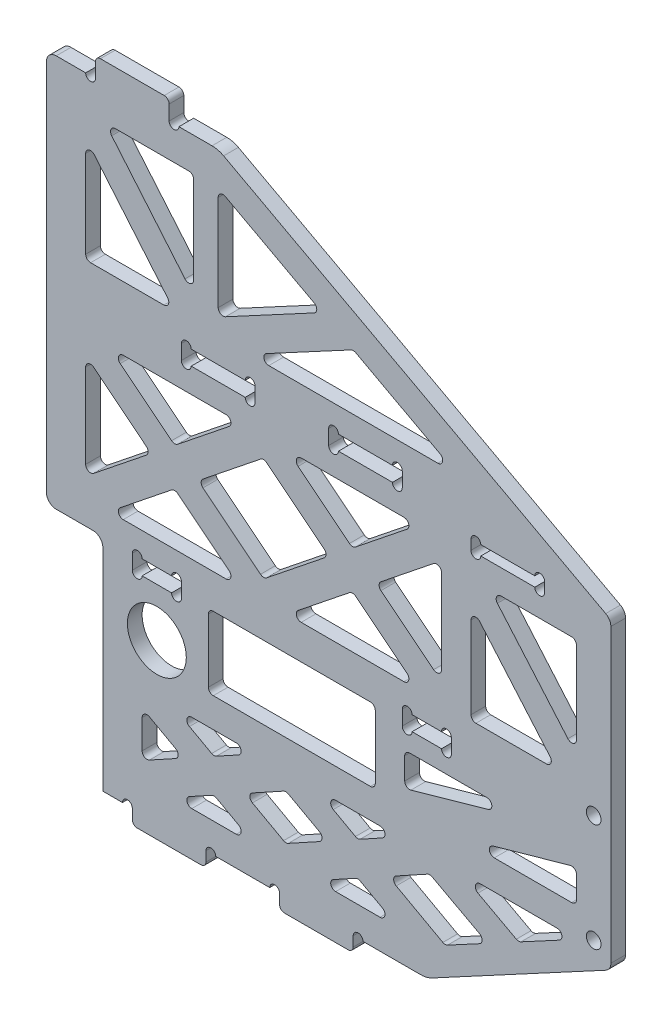
SolidWorks part; units mm, degrees
material "Thornel Mat VMA"
ref_plane "前视基准面" through (0, 0, 0) normal (0, 0, 1) x (1, 0, 0)
ref_plane "上视基准面" through (0, 0, 0) normal (0, 1, 0) x (1, 0, 0)
ref_plane "右视基准面" through (0, 0, 0) normal (1, 0, 0) x (0, 0, -1)
sketch "草图1" plane through (0, 0, 0) normal (0, 0, 1) x (1, 0, 0)
  line L0 (17.5, 83) -> (97.5, 40)
  line L1 (0, 0) -> (10, 0)
  line L2 (0, 0) -> (0, 3)
  line L3 (0, 3) -> (10, 3)
  line L4 (10, 0) -> (10, 3)
  line L5 (-17.5, 83) -> (-7.5, 83)
  line L11 (97.5, -21.8) -> (60, -42)
  line L12 (0, -42) -> (-6, -42)
  line L13 (0, -42) -> (0, 0) construction
  line L15 (97.5, -21.8) -> (97.5, 40)
  line L17 (97.5, 40) -> (84, 40) construction
  line L18 (-6, 3) -> (-6, -42)
  line L20 (55, 0) -> (65, 0)
  line L21 (65, 0) -> (65, 3)
  line L22 (65, 3) -> (55, 3)
  line L23 (55, 3) -> (55, 0)
  line L25 (94, -18.3) -> (94, 3.7) construction
  line L27 (7.5, 83) -> (7.5, 87)
  line L28 (40, 42) -> (55, 42)
  line L29 (55, 42) -> (55, 45)
  line L30 (55, 45) -> (40, 45)
  line L31 (40, 45) -> (40, 42)
  line L36 (45, -45) -> (45, -42)
  line L37 (45, -45) -> (30, -45)
  line L38 (60, -42) -> (45, -42)
  line L39 (30, -45) -> (30, -42)
  line L40 (30, -42) -> (15, -42)
  line L41 (15, -45) -> (15, -42)
  line L42 (15, -45) -> (0, -45)
  line L43 (0, -45) -> (0, -42)
  line L44 (10, 42) -> (25, 42)
  line L45 (25, 42) -> (25, 45)
  line L46 (25, 45) -> (10, 45)
  line L47 (10, 45) -> (10, 42)
  line L48 (-6, 3) -> (-17.5, 3)
  line L49 (-17.5, 3) -> (-17.5, 83)
  line L50 (7.5, 87) -> (-7.5, 87)
  line L51 (-7.5, 83) -> (-7.5, 87)
  line L52 (7.5, 83) -> (17.5, 83)
  line L60 (69, 38) -> (84, 38)
  line L61 (84, 38) -> (84, 40)
  line L62 (84, 40) -> (69, 40)
  line L63 (69, 40) -> (69, 38)
  circle A2 centre (94, -18.3) radius 1.5
  circle A3 centre (94, 3.7) radius 1.5
  dimension "D15" = 94
  dimension "D16" = 23.7
  dimension "D17" = 61.8
  dimension "D18" = 3.5
  dimension "D19" = 3
  dimension "D20" = 3.5
  dimension "D1" = 3
  dimension "D2" = 45
  dimension "D3" = 10
  dimension "D4" = 42
  dimension "D5" = 6
  dimension "D6" = 3
  dimension "D7" = 15
  dimension "D8" = 15
  dimension "D9" = 11.5
  dimension "D10" = 10
  dimension "D11" = 80
  dimension "D12" = 35
  dimension "D13" = 4
  dimension "D14" = 15
  dimension "D21" = 15
  dimension "D22" = 3
  dimension "D23" = 15
  dimension "D24" = 39
  dimension "D25" = 10
  dimension "D26" = 22
  dimension "D27" = 13.5
  dimension "D28" = 15
  dimension "D29" = 2
extrude "凸台-拉伸1" add sketch "草图1" along normal blind 3
sketch "草图3" plane through (0, 0, 3) normal (0, 0, 1) x (1, 0, 0)
  line L0 (17.5, 76.1882) -> (17.5, 50)
  line L1 (17.5, 50) -> (66.2222, 50)
  line L2 (66.2222, 50) -> (17.5, 76.1882)
  line L3 (97.5, 40) -> (17.5, 83) construction
  line L4 (55, 45) -> (40, 45) construction
  line L5 (90.5, -13.8914) -> (90.5, -4)
  line L6 (-9.5, 76.1882) -> (12.5, 76.1882)
  line L7 (-9.5, 76.1882) -> (-9.5, 50)
  line L8 (-9.5, 50) -> (12.5, 50)
  line L9 (12.5, 76.1882) -> (12.5, 50)
  line L10 (-9.5, 37) -> (63, 37)
  line L11 (-9.5, 37) -> (-9.5, 8)
  line L12 (-9.5, 8) -> (63, 8)
  line L13 (63, 37) -> (63, 8)
  line L14 (69, 33) -> (90.5, 33)
  line L15 (69, 33) -> (69, 8)
  line L16 (69, 8) -> (90.5, 8)
  line L17 (90.5, 33) -> (90.5, 8)
  line L18 (2, -19.8914) -> (90.5, -19.8914)
  line L19 (2, -19.8914) -> (2, -36)
  line L20 (2, -36) -> (60.5954, -36)
  line L21 (90.5, -19.8914) -> (60.5954, -36)
  line L22 (15, -42) -> (30, -42) construction
  line L23 (-6, 3) -> (-6, -42) construction
  line L25 (10, 3) -> (0, 3) construction
  line L26 (-17.5, 83) -> (-17.5, 3) construction
  line L27 (40, 42) -> (55, 42) construction
  line L28 (65, 3) -> (55, 3) construction
  line L29 (97.5, -21.8) -> (97.5, 40) construction
  line L30 (69, 38) -> (84, 38) construction
  line L32 (60, -42) -> (97.5, -21.8) construction
  line L33 (69, 40) -> (69, 38) construction
  line L34 (15.5, 1) -> (49.5, 1)
  line L35 (15.5, 1) -> (15.5, -13.8914)
  line L36 (15.5, -13.8914) -> (49.5, -13.8914)
  line L37 (49.5, 1) -> (49.5, -13.8914)
  line L38 (10, 0) -> (10, 3) construction
  line L39 (55, 3) -> (55, 0) construction
  line L40 (55.5, -13.8914) -> (90.5, -13.8914)
  line L41 (55.5, -13.8914) -> (55.5, -4)
  line L42 (55.5, -4) -> (90.5, -4)
  line L43 (55, 0) -> (65, 0) construction
  circle A0 centre (5, -9.8914) radius 6
  dimension "D20" = 12
  dimension "D21" = 10
  dimension "D22" = 11
  dimension "D1" = 5
  dimension "D2" = 6
  dimension "D3" = 6
  dimension "D4" = 8
  dimension "D5" = 6
  dimension "D6" = 5
  dimension "D7" = 8
  dimension "D8" = 5
  dimension "D9" = 5
  dimension "D10" = 7
  dimension "D11" = 6
  dimension "D12" = 5
  dimension "D13" = 5
  dimension "D14" = 5
  dimension "D15" = 7
  dimension "D16" = 6
  dimension "D17" = 5.5
  dimension "D18" = 5.5
  dimension "D19" = 4
extrude "切除-拉伸2" cut sketch "草图3" against normal through all
sketch "草图4" plane through (0, 0, 3) normal (0, 0, 1) x (1, 0, 0)
  line L0 (-9.5, 76.1882) -> (12.5, 50)
  line L1 (17.5, 50) -> (45.0294, 64.797)
  line L2 (66.2222, 50) -> (17.5, 76.1882) construction
  line L3 (-9.5, 37) -> (26.75, 8)
  line L4 (-9.5, 8) -> (63, 8) construction
  line L5 (63, 8) -> (26.75, 37)
  line L6 (63, 37) -> (-9.5, 37) construction
  line L7 (26.75, 37) -> (-9.5, 8)
  line L8 (26.75, 8) -> (63, 37)
  line L9 (90.5, 8) -> (69, 33)
  line L10 (2, -19.8914) -> (31.2977, -36)
  line L11 (2, -36) -> (60.5954, -36) construction
  line L12 (60.5954, -36) -> (31.2977, -19.8914)
  line L13 (90.5, -19.8914) -> (2, -19.8914) construction
  line L14 (60.5954, -36) -> (63.2243, -37.4454)
  line L15 (60.5954, -19.8914) -> (31.2977, -36)
  line L16 (31.2977, -19.8914) -> (2, -36)
  line L17 (60.5954, -19.8914) -> (75.5477, -27.9457)
  line L18 (60.5954, -36) -> (90.5, -19.8914) construction
  line L19 (75.5477, -27.9457) -> (78.1889, -29.3684)
  line L20 (55.5, -13.8914) -> (90.5, -4)
  point P10 (41.8611, 63.0941)
  dimension "D1" = 3
  dimension "D2" = 3
extrude "拉伸-薄壁1" add sketch "草图4" against normal up to surface (3 mm away) thin up to face at (38.7739, -27.9457, 0) thin type mid plane wall 6
sketch "草图2" plane through (0, 0, 3) normal (0, 0, 1) x (1, 0, 0)
  line L0 (-7.5, 83) -> (-17.5, 83) construction
  line L1 (17.5, 83) -> (7.5, 83) construction
  line L2 (25, 45) -> (10, 45) construction
  line L3 (10, 42) -> (25, 42) construction
  line L4 (55, 45) -> (40, 45) construction
  line L5 (40, 42) -> (55, 42) construction
  line L6 (84, 40) -> (69, 40) construction
  line L7 (69, 38) -> (84, 38) construction
  line L8 (10, 3) -> (0, 3) construction
  line L9 (0, 0) -> (10, 0) construction
  line L10 (65, 3) -> (55, 3) construction
  line L11 (55, 0) -> (65, 0) construction
  line L12 (-6, -42) -> (0, -42) construction
  line L13 (15, -42) -> (30, -42) construction
  line L14 (45, -42) -> (60, -42) construction
  line L15 (69, 38) -> (71, 38)
  line L16 (84, 40) -> (82, 40)
  line L17 (71, 40) -> (69, 40)
  line L18 (82, 38) -> (84, 38)
  circle A0 centre (-8.5, 83) radius 1
  circle A1 centre (8.5, 83) radius 1
  circle A2 centre (11, 45) radius 1
  circle A3 centre (24, 45) radius 1
  circle A4 centre (11, 42) radius 1
  circle A5 centre (24, 42) radius 1
  circle A6 centre (41, 45) radius 1
  circle A7 centre (41, 42) radius 1
  circle A8 centre (54, 45) radius 1
  circle A9 centre (54, 42) radius 1
  arc A10 (71, 40) -> (69, 40) centre (70, 40) ccw
  arc A11 (69, 38) -> (71, 38) centre (70, 38) ccw
  arc A12 (84, 40) -> (82, 40) centre (83, 40) ccw
  arc A13 (82, 38) -> (84, 38) centre (83, 38) ccw
  circle A14 centre (1, 3) radius 1
  circle A15 centre (1, 0) radius 1
  circle A16 centre (9, 3) radius 1
  circle A17 centre (9, 0) radius 1
  circle A18 centre (56, 3) radius 1
  circle A19 centre (56, 0) radius 1
  circle A20 centre (64, 3) radius 1
  circle A21 centre (64, 0) radius 1
  circle A22 centre (-1, -42) radius 1
  circle A23 centre (16, -42) radius 1
  circle A24 centre (29, -42) radius 1
  circle A25 centre (46, -42) radius 1
  dimension "D1" = 2
extrude "切除-拉伸1" cut sketch "草图2" against normal through all
fillet "圆角1" radius 1 82 edges at (30, -45, 1.5) (45, -45, 1.5) (15, -45, 1.5) (0, -45, 1.5) (7.5, 87, 1.5) (-7.5, 87, 1.5) (-5.5819, 76.1882, 1.5) (12.5, 76.1882, 1.5) (12.5, 54.664, 1.5) (-9.5, 50, 1.5) (-9.5, 71.5242, 1.5) (8.5819, 50, 1.5) (17.5, 53.4059, 1.5) (17.5, 76.1882, 1.5) (38.6928, 64.797, 1.5) (66.2222, 50, 1.5) (23.8366, 50, 1.5) (45.0294, 61.3911, 1.5) (26.75, 11.8419, 1.5) (13.4273, 22.5, 1.5) (26.75, 33.1581, 1.5) (40.0727, 22.5, 1.5) (31.5523, 8, 1.5) (44.875, 18.6581, 1.5) (58.1977, 8, 1.5) (-4.6977, 37, 1.5) (21.9477, 37, 1.5) (8.625, 18.6581, 1.5) (21.9477, 8, 1.5) (-4.6977, 8, 1.5) (49.6773, 22.5, 1.5) (63, 33.1581, 1.5) (63, 11.8419, 1.5) (-9.5, 33.1581, 1.5) (3.8227, 22.5, 1.5) (-9.5, 11.8419, 1.5) (58.1977, 37, 1.5) (44.875, 26.3419, 1.5) (31.5523, 37, 1.5) (86.5432, 8, 1.5) (69, 8, 1.5) (69, 28.3991, 1.5) (90.5, 33, 1.5) (90.5, 12.6009, 1.5) (72.9568, 33, 1.5) (31.2977, -23.315, 1.5) (39.7199, -27.9457, 1.5) (31.2977, -32.5764, 1.5) (22.8755, -27.9457, 1.5) (37.5244, -36, 1.5) (45.9466, -31.3693, 1.5) (52.1732, -27.9457, 1.5) (60.6101, -23.3069, 1.5) (16.6489, -31.3693, 1.5) (25.0711, -36, 1.5) (8.2266, -36, 1.5) (10.4222, -27.9457, 1.5) (2, -32.5764, 1.5) (2, -23.315, 1.5) (54.3688, -19.8914, 1.5) (45.9466, -24.5221, 1.5) (66.9213, -19.8914, 1.5) (90.5, -19.8914, 1.5) (8.2266, -19.8914, 1.5) (25.0711, -19.8914, 1.5) (37.5244, -19.8914, 1.5) (16.6489, -24.5221, 1.5) (54.3688, -36, 1.5) (8.625, 26.3419, 1.5) (15.5, 1, 1.5) (15.5, -13.8914, 1.5) (49.5, -13.8914, 1.5) (49.5, 1, 1.5) (78.7107, -26.2419, 1.5) (72.3848, -29.6495, 1.5) (63.7407, -34.3058, 1.5) (66.5311, -13.8914, 1.5) (90.5, -13.8914, 1.5) (90.5, -7.1175, 1.5) (55.5, -10.7739, 1.5) (79.4689, -4, 1.5) (55.5, -4, 1.5)
fillet "圆角2" radius 2 5 edges at (-6, 3, 1.5) (-17.5, 3, 1.5) (97.5, -21.8, 1.5) (97.5, 40, 1.5) (-17.5, 83, 1.5)
fillet "圆角3" radius 5 2 edges at (17.5, 83, 1.5) (60, -42, 1.5)
